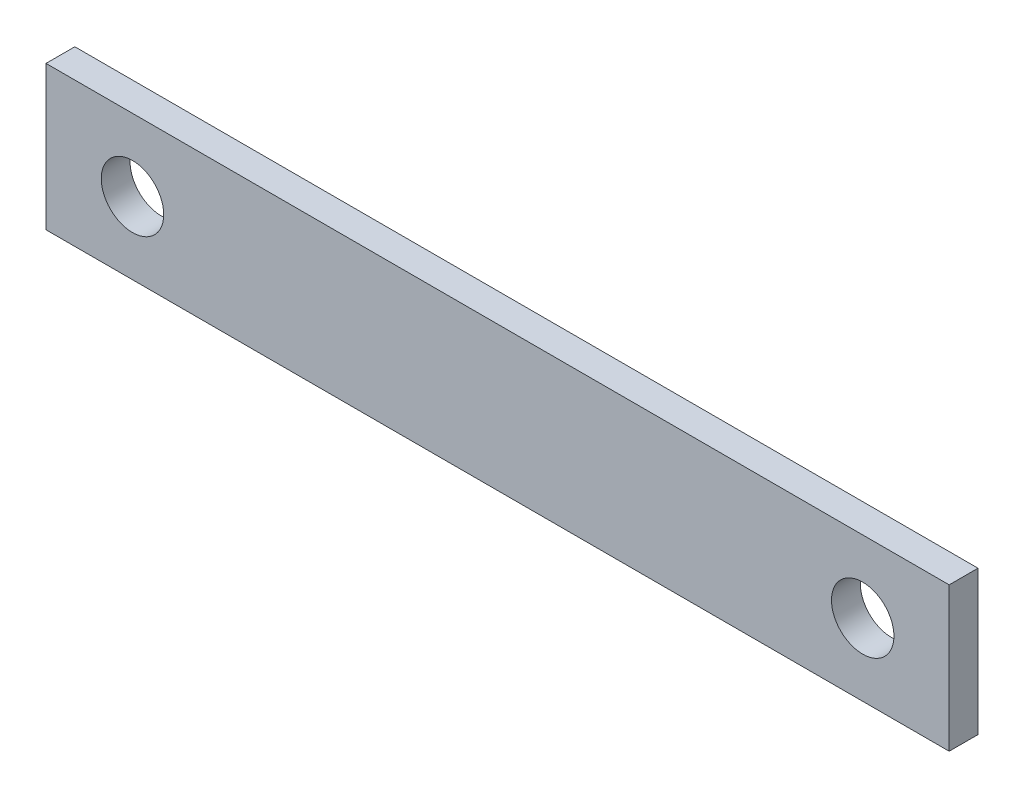
SolidWorks part; units mm, degrees
ref_plane "Alzado" through (0, 0, 0) normal (0, 0, 1) x (1, 0, 0)
ref_plane "Planta" through (0, 0, 0) normal (0, 1, 0) x (1, 0, 0)
ref_plane "Vista lateral" through (0, 0, 0) normal (1, 0, 0) x (0, 0, -1)
sketch "Croquis1" plane through (0, 0, 0) normal (0, 0, 1) x (1, 0, 0)
  line L1 (47, 7.5) -> (-47, 7.5)
  line L2 (47, 7.5) -> (47, -7.5)
  line L3 (47, -7.5) -> (-47, -7.5)
  line L4 (-47, 7.5) -> (-47, -7.5)
  line L5 (47, 7.5) -> (-47, -7.5) construction
  line L6 (47, -7.5) -> (-47, 7.5) construction
  point P0 (0, 0)
  dimension "D1" = 15
  dimension "D2" = 94
extrude "Saliente-Extruir1" add sketch "Croquis1" along normal blind 3
sketch "Croquis2" plane through (0, 0, 3) normal (0, 0, 1) x (1, 0, 0)
  circle A0 centre (-38, 0) radius 3.25
  circle A1 centre (38, 0) radius 3.25
  dimension "D1" = 6.5
  dimension "D2" = 6.5
  dimension "D3" = 38
  dimension "D4" = 38
extrude "Cortar-Extruir1" cut sketch "Croquis2" against normal up to next
